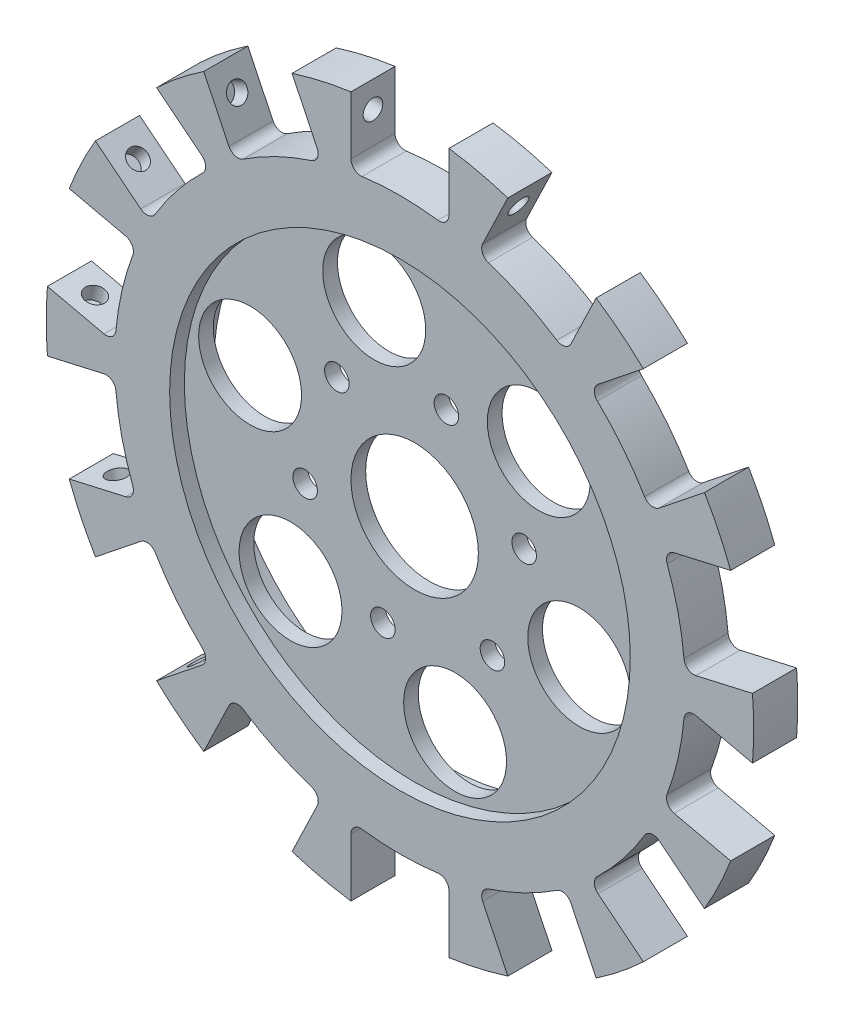
SolidWorks part; units mm, degrees
material "AISI 1020 钢，冷轧"
ref_plane "前视基准面" through (0, 0, 0) normal (0, 0, 1) x (1, 0, 0)
ref_plane "上视基准面" through (0, 0, 0) normal (0, 1, 0) x (1, 0, 0)
ref_plane "右视基准面" through (0, 0, 0) normal (1, 0, 0) x (0, 0, -1)
sketch "草图1" plane through (0, 0, 0) normal (0, 0, 1) x (1, 0, 0)
  circle A0 centre (0, 0) radius 72.2
  dimension "D1" = 144.4
extrude "凸台-拉伸1" add sketch "草图1" along normal blind 9
sketch "草图2" plane through (0, 0, 9) normal (0, 0, 1) x (1, 0, 0)
  line L0 (0, 72.2) -> (0, -72.2) construction
  line L1 (-10, 71.5041) -> (-10, 59.6661)
  line L2 (10, 71.5041) -> (10, 59.6661)
  line L3 (22.0148, 68.7618) -> (16.8784, 58.0961)
  line L4 (40.0342, 60.0842) -> (34.8978, 49.4184)
  line L5 (-10, 72.2) -> (-10, -72.2) construction
  line L6 (49.6693, 52.4004) -> (40.4139, 45.0195)
  line L7 (10, 72.2) -> (10, -72.2) construction
  line L8 (62.1391, 36.7638) -> (52.8837, 29.3829)
  line L9 (67.4862, 25.6604) -> (55.9449, 23.0262)
  line L10 (71.9366, 6.1619) -> (60.3953, 3.5277)
  line L11 (71.9366, -6.1619) -> (60.3953, -3.5277)
  line L12 (67.4862, -25.6604) -> (55.9449, -23.0262)
  line L13 (62.1391, -36.7638) -> (52.8837, -29.3829)
  line L14 (49.6693, -52.4004) -> (40.4139, -45.0195)
  line L15 (40.0342, -60.0842) -> (34.8978, -49.4184)
  line L16 (22.0148, -68.7618) -> (16.8784, -58.0961)
  line L17 (10, -71.5041) -> (10, -59.6661)
  line L18 (-10, -71.5041) -> (-10, -59.6661)
  line L19 (-22.0148, -68.7618) -> (-16.8784, -58.0961)
  line L20 (-40.0342, -60.0842) -> (-34.8978, -49.4184)
  line L21 (-49.6693, -52.4004) -> (-40.4139, -45.0195)
  line L22 (-62.1391, -36.7638) -> (-52.8837, -29.3829)
  line L23 (-67.4862, -25.6604) -> (-55.9449, -23.0262)
  line L24 (-71.9366, -6.1619) -> (-60.3953, -3.5277)
  line L25 (-71.9366, 6.1619) -> (-60.3953, 3.5277)
  line L26 (-67.4862, 25.6604) -> (-55.9449, 23.0262)
  line L27 (-62.1391, 36.7638) -> (-52.8837, 29.3829)
  line L28 (-49.6693, 52.4004) -> (-40.4139, 45.0195)
  line L29 (-40.0342, 60.0842) -> (-34.8978, 49.4184)
  line L30 (-22.0148, 68.7618) -> (-16.8784, 58.0961)
  arc A0 (7.7342, 57.6838) -> (-7.7342, 57.6838) centre (0, 0) ccw
  circle A1 centre (0, 0) radius 72.2 construction
  arc A2 (10, 71.5041) -> (-10, 71.5041) centre (0, 0) ccw
  arc A3 (7.7342, 57.6838) -> (10, 59.6661) centre (8, 59.6661) ccw
  arc A4 (-7.7342, 57.6838) -> (-10, 59.6661) centre (-8, 59.6661) cw
  arc A5 (31.9964, 48.6156) -> (18.0598, 55.3271) centre (0, 0) ccw
  arc A6 (40.0342, 60.0842) -> (22.0148, 68.7618) centre (0, 0) ccw
  arc A7 (31.9964, 48.6156) -> (34.8978, 49.4184) centre (33.0959, 50.2862) ccw
  arc A8 (18.0598, 55.3271) -> (16.8784, 58.0961) centre (18.6804, 57.2283) cw
  arc A9 (49.9212, 29.9184) -> (40.2768, 42.0121) centre (0, 0) ccw
  arc A10 (62.1391, 36.7638) -> (49.6693, 52.4004) centre (0, 0) ccw
  arc A11 (49.9212, 29.9184) -> (52.8837, 29.3829) centre (51.6367, 30.9465) ccw
  arc A12 (40.2768, 42.0121) -> (40.4139, 45.0195) centre (41.6609, 43.4558) cw
  arc A13 (57.9586, 5.2955) -> (54.5165, 20.3762) centre (0, 0) ccw
  arc A14 (71.9366, 6.1619) -> (67.4862, 25.6604) centre (0, 0) ccw
  arc A15 (57.9586, 5.2955) -> (60.3953, 3.5277) centre (59.9503, 5.4775) ccw
  arc A16 (54.5165, 20.3762) -> (55.9449, 23.0262) centre (56.39, 21.0764) cw
  arc A17 (54.5165, -20.3762) -> (57.9586, -5.2955) centre (0, 0) ccw
  arc A18 (67.4862, -25.6604) -> (71.9366, -6.1619) centre (0, 0) ccw
  arc A19 (54.5165, -20.3762) -> (55.9449, -23.0262) centre (56.39, -21.0764) ccw
  arc A20 (57.9586, -5.2955) -> (60.3953, -3.5277) centre (59.9503, -5.4775) cw
  arc A21 (40.2768, -42.0121) -> (49.9212, -29.9184) centre (0, 0) ccw
  arc A22 (49.6693, -52.4004) -> (62.1391, -36.7638) centre (0, 0) ccw
  arc A23 (40.2768, -42.0121) -> (40.4139, -45.0195) centre (41.6609, -43.4558) ccw
  arc A24 (49.9212, -29.9184) -> (52.8837, -29.3829) centre (51.6367, -30.9465) cw
  arc A25 (18.0598, -55.3271) -> (31.9964, -48.6156) centre (0, 0) ccw
  arc A26 (22.0148, -68.7618) -> (40.0342, -60.0842) centre (0, 0) ccw
  arc A27 (18.0598, -55.3271) -> (16.8784, -58.0961) centre (18.6804, -57.2283) ccw
  arc A28 (31.9964, -48.6156) -> (34.8978, -49.4184) centre (33.0959, -50.2862) cw
  arc A29 (-7.7342, -57.6838) -> (7.7342, -57.6838) centre (0, 0) ccw
  arc A30 (-10, -71.5041) -> (10, -71.5041) centre (0, 0) ccw
  arc A31 (-7.7342, -57.6838) -> (-10, -59.6661) centre (-8, -59.6661) ccw
  arc A32 (7.7342, -57.6838) -> (10, -59.6661) centre (8, -59.6661) cw
  arc A33 (-31.9964, -48.6156) -> (-18.0598, -55.3271) centre (0, 0) ccw
  arc A34 (-40.0342, -60.0842) -> (-22.0148, -68.7618) centre (0, 0) ccw
  arc A35 (-31.9964, -48.6156) -> (-34.8978, -49.4184) centre (-33.0959, -50.2862) ccw
  arc A36 (-18.0598, -55.3271) -> (-16.8784, -58.0961) centre (-18.6804, -57.2283) cw
  arc A37 (-49.9212, -29.9184) -> (-40.2768, -42.0121) centre (0, 0) ccw
  arc A38 (-62.1391, -36.7638) -> (-49.6693, -52.4004) centre (0, 0) ccw
  arc A39 (-49.9212, -29.9184) -> (-52.8837, -29.3829) centre (-51.6367, -30.9465) ccw
  arc A40 (-40.2768, -42.0121) -> (-40.4139, -45.0195) centre (-41.6609, -43.4558) cw
  arc A41 (-57.9586, -5.2955) -> (-54.5165, -20.3762) centre (0, 0) ccw
  arc A42 (-71.9366, -6.1619) -> (-67.4862, -25.6604) centre (0, 0) ccw
  arc A43 (-57.9586, -5.2955) -> (-60.3953, -3.5277) centre (-59.9503, -5.4775) ccw
  arc A44 (-54.5165, -20.3762) -> (-55.9449, -23.0262) centre (-56.39, -21.0764) cw
  arc A45 (-54.5165, 20.3762) -> (-57.9586, 5.2955) centre (0, 0) ccw
  arc A46 (-67.4862, 25.6604) -> (-71.9366, 6.1619) centre (0, 0) ccw
  arc A47 (-54.5165, 20.3762) -> (-55.9449, 23.0262) centre (-56.39, 21.0764) ccw
  arc A48 (-57.9586, 5.2955) -> (-60.3953, 3.5277) centre (-59.9503, 5.4775) cw
  arc A49 (-40.2768, 42.0121) -> (-49.9212, 29.9184) centre (0, 0) ccw
  arc A50 (-49.6693, 52.4004) -> (-62.1391, 36.7638) centre (0, 0) ccw
  arc A51 (-40.2768, 42.0121) -> (-40.4139, 45.0195) centre (-41.6609, 43.4558) ccw
  arc A52 (-49.9212, 29.9184) -> (-52.8837, 29.3829) centre (-51.6367, 30.9465) cw
  arc A53 (-18.0598, 55.3271) -> (-31.9964, 48.6156) centre (0, 0) ccw
  arc A54 (-22.0148, 68.7618) -> (-40.0342, 60.0842) centre (0, 0) ccw
  arc A55 (-18.0598, 55.3271) -> (-16.8784, 58.0961) centre (-18.6804, 57.2283) ccw
  arc A56 (-31.9964, 48.6156) -> (-34.8978, 49.4184) centre (-33.0959, 50.2862) cw
  point P125 (0, 0)
  dimension "D1" = 14
  dimension "D4" = 2
  dimension "D2" = 10
  dimension "D3" = 10
  dimension "D5" = 14
extrude "切除-拉伸2" cut sketch "草图2" against normal blind 9
sketch "草图3" plane through (0, 0, 9) normal (0, 0, 1) x (1, 0, 0)
  circle A0 centre (0, 0) radius 47
  dimension "D1" = 94
extrude "切除-拉伸3" cut sketch "草图3" against normal blind 3
sketch "草图4" plane through (0, 0, 0) normal (0, 0, -1) x (-1, 0, 0)
  circle A0 centre (0, 0) radius 47
  dimension "D1" = 94
extrude "切除-拉伸4" cut sketch "草图4" against normal blind 3
sketch "草图5" plane through (0, 0, 3) normal (0, 0, -1) x (-1, 0, 0)
  line L0 (0, 0) -> (15.8718, 16.6459) construction
  line L1 (-16.3968, 55.8425) -> (0, 0) construction
  line L2 (0, 0) -> (8.2516, 34.0134) construction
  line L4 (-16.3968, 55.8425) -> (-18.6863, 63.6396) construction
  circle A0 centre (0, 0) radius 13
  circle A1 centre (0, 0) radius 23 construction
  circle A2 centre (-6.4798, 22.0683) radius 2.5
  circle A3 centre (15.8718, 16.6459) radius 2.5
  circle A4 centre (22.3517, -5.4225) radius 2.5
  circle A5 centre (6.4798, -22.0683) radius 2.5
  circle A6 centre (-15.8718, -16.6459) radius 2.5
  circle A7 centre (-22.3517, 5.4225) radius 2.5
  circle A8 centre (0, 0) radius 35 construction
  circle A9 centre (8.2516, 34.0134) radius 10.5
  circle A10 centre (33.5823, 9.8606) radius 10.5
  circle A11 centre (25.3307, -24.1528) radius 10.5
  circle A12 centre (-8.2516, -34.0134) radius 10.5
  circle A13 centre (-33.5823, -9.8606) radius 10.5
  circle A14 centre (-25.3307, 24.1528) radius 10.5
  circle A15 centre (0, 0) radius 47 construction
  arc A16 (-18.0598, 55.3271) -> (-31.9964, 48.6156) centre (0, 0) ccw construction
  dimension "D1" = 5
  dimension "D2" = 46
  dimension "D3" = 30
  dimension "D5" = 70
  dimension "D6" = 30
  dimension "D7" = 21
  dimension "D9" = 26
  dimension "D4" = 6
  dimension "D8" = 6
sketch "草图6" plane through (-10, 0, 0) normal (1, 0, 0) x (0, 0, -1)
  line L0 (0, 71.5041) -> (-9, 71.5041) construction
  line L1 (0, 71.5041) -> (0, 59.6661) construction
  circle A0 centre (-4.5, 66.1541) radius 2
  dimension "D1" = 4
  dimension "D2" = 5.35
  dimension "D3" = 4.5
extrude "切除-拉伸6" cut sketch "草图6" against normal blind 3
pattern_circular "阵列(圆周)1" count 14 over 360 about axis through (0, 0, 0) along (0, 0, 1) of "切除-拉伸6"
extrude "切除-拉伸7" cut sketch "草图5" against normal through all
